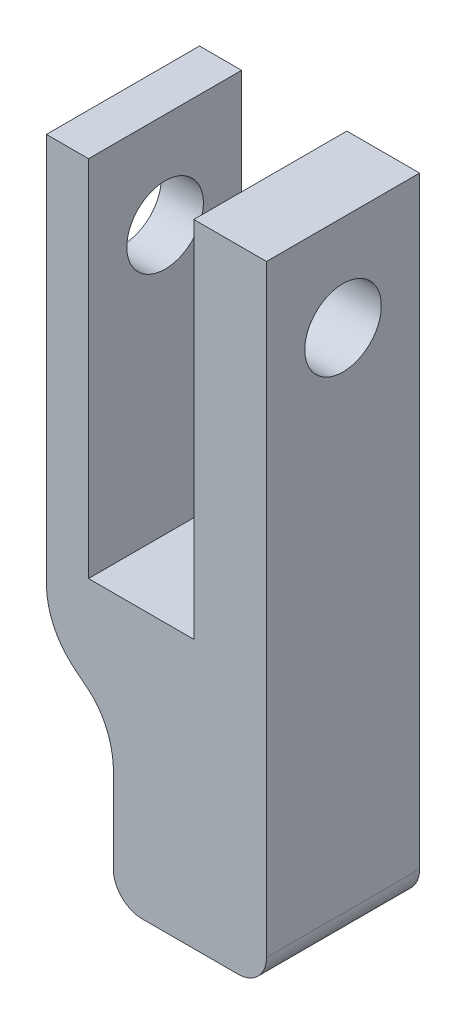
SolidWorks part; units mm, degrees
ref_plane "前视基准面" through (0, 0, 0) normal (0, 0, 1) x (1, 0, 0)
ref_plane "上视基准面" through (0, 0, 0) normal (0, 1, 0) x (1, 0, 0)
ref_plane "右视基准面" through (0, 0, 0) normal (1, 0, 0) x (0, 0, -1)
sketch "草图1" plane through (0, 0, 0) normal (0, 0, 1) x (1, 0, 0)
  line L0 (2.874, 8.2525) -> (2.874, -7.4975)
  line L1 (2.124, -8.2475) -> (-0.376, -8.2475)
  line L2 (-1.126, -7.4975) -> (-1.126, -5.2319)
  line L3 (-2.876, -1.9247) -> (-2.876, 8.2525)
  line L4 (-2.876, 8.2525) -> (-1.776, 8.2525)
  line L5 (-1.776, 8.2525) -> (-1.776, -1.2475)
  line L6 (-1.776, -1.2475) -> (0.974, -1.2475)
  line L7 (0.974, -1.2475) -> (0.974, 8.2525)
  line L8 (0.974, 8.2525) -> (2.874, 8.2525)
  spline S0 degree 3 poles (2.874, -7.4975) (2.8764, -7.7034) (2.6994, -8.0967) (2.3078, -8.2487) (2.124, -8.2475) knots 0 0 0 0 0.528701 1 1 1 1
  spline S1 degree 3 poles (-0.376, -8.2475) (-0.7787, -8.2574) (-1.1358, -7.9002) (-1.126, -7.4975) knots 0 0 0 0 1 1 1 1
  spline S2 degree 3 poles (-1.126, -5.2319) (-1.1366, -4.7517) (-1.3784, -4.0238) (-2.104, -3.524) (-2.6805, -2.9605) (-2.8764, -2.3411) (-2.876, -1.9247) knots 0 0 0 0 0.38162 0.529035 0.676294 1 1 1 1
extrude "凸台-拉伸1" add sketch "草图1" along normal blind 4
sketch "草图2" plane through (-2.876, 0, 0) normal (-1, 0, 0) x (0, 0, 1)
  line L0 (2, 8.2525) -> (2, 5.7525) construction
  line L1 (4, 8.2525) -> (0, 8.2525) construction
  circle A0 centre (2, 5.7525) radius 1
extrude "切除-拉伸1" cut sketch "草图2" against normal blind 10
sketch "草图3" plane through (0, -8.2475, 0) normal (0, -1, 0) x (1, 0, 0)
  line L0 (-0.376, 0) -> (2.124, 0) construction
  line L1 (2.124, 4) -> (2.124, 0) construction
  circle A0 centre (0.874, 2) radius 1
  dimension "D1" = 2
  dimension "D2" = 1.25
extrude "切除-拉伸2" cut sketch "草图3" against normal blind 5
